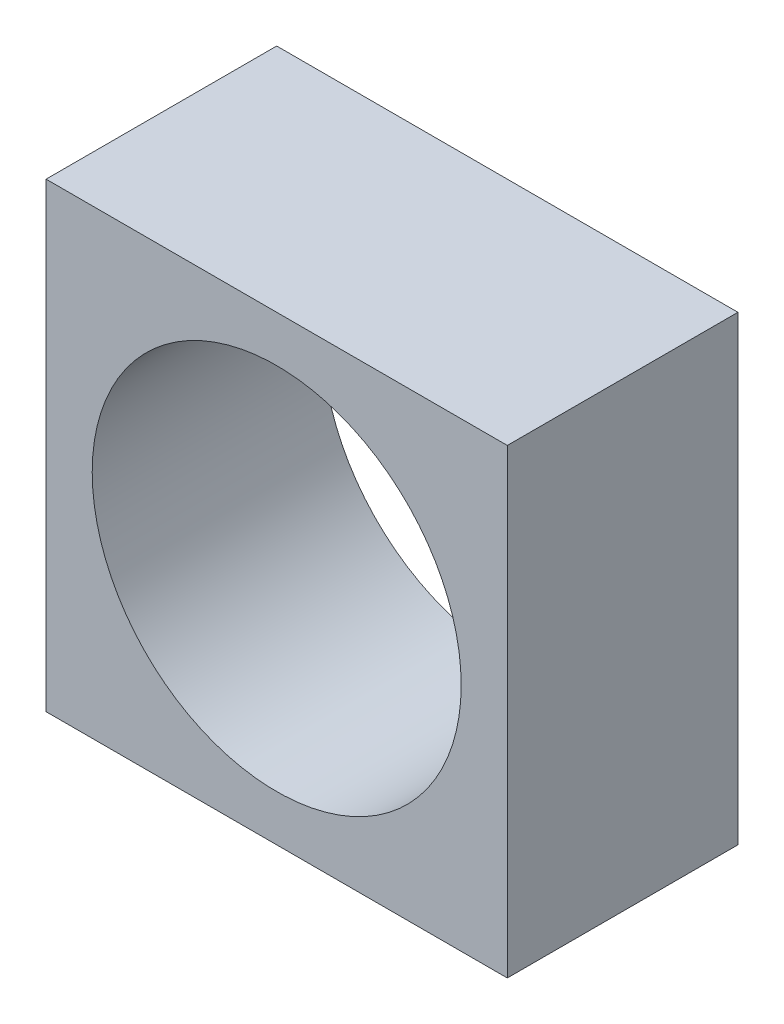
SolidWorks part; units mm, degrees
material "201.0-T7 Insulated Mold Casting (SS)"
ref_plane "Front Plane" through (0, 0, 0) normal (0, 0, 1) x (1, 0, 0)
ref_plane "Top Plane" through (0, 0, 0) normal (0, 1, 0) x (1, 0, 0)
ref_plane "Right Plane" through (0, 0, 0) normal (1, 0, 0) x (0, 0, -1)
sketch "Sketch1" plane through (0, 0, 0) normal (0, 0, 1) x (1, 0, 0)
  line L1 (10, 10) -> (-10, 10)
  line L2 (10, 10) -> (10, -10)
  line L3 (10, -10) -> (-10, -10)
  line L4 (-10, 10) -> (-10, -10)
  line L5 (10, 10) -> (-10, -10) construction
  line L6 (10, -10) -> (-10, 10) construction
  point P0 (0, 0)
ref_plane "Plane1" through (0, 0, 10) normal (0, 0, 1) x (1, 0, 0)
sketch "Sketch2" plane through (0, 0, 10) normal (0, 0, 1) x (1, 0, 0)
  line L1 (10, 10) -> (-10, 10)
  line L2 (10, 10) -> (10, -10)
  line L3 (10, -10) -> (-10, -10)
  line L4 (-10, 10) -> (-10, -10)
  line L5 (10, 10) -> (-10, -10) construction
  line L6 (10, -10) -> (-10, 10) construction
  point P0 (0, 0)
sketch "Sketch3" plane through (0, 0, 0) normal (0, 0, 1) x (1, 0, 0)
  circle A0 centre (0, 0) radius 8
loft "Loft1" add profiles "Sketch1", "Sketch2"
extrude "Cut-Extrude1" cut sketch "Sketch3" against normal through all both and the other way through all
